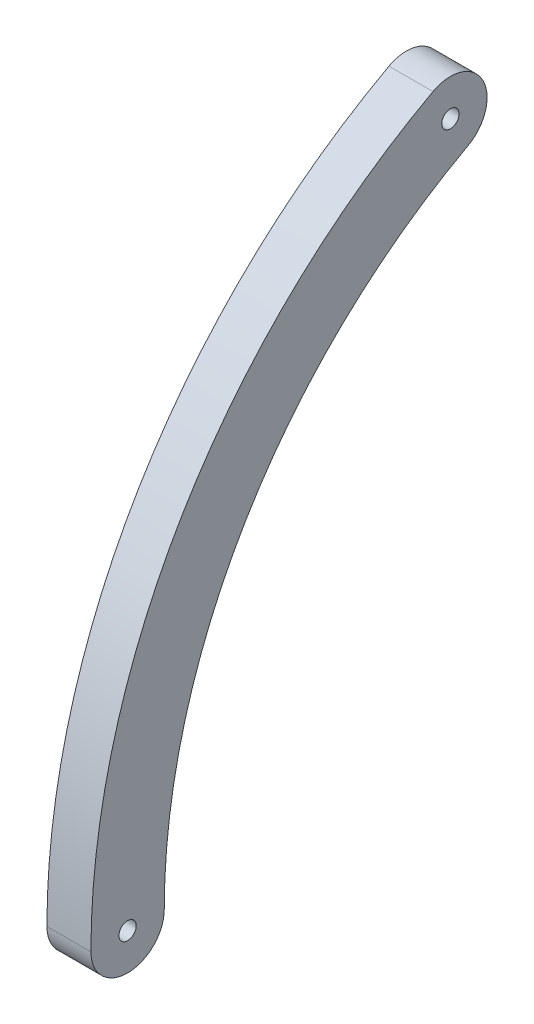
SolidWorks part; units mm, degrees
material "ABS"
ref_plane "Front Plane" through (0, 0, 0) normal (0, 0, 1) x (1, 0, 0)
ref_plane "Top Plane" through (0, 0, 0) normal (0, 1, 0) x (1, 0, 0)
ref_plane "Right Plane" through (0, 0, 0) normal (1, 0, 0) x (0, 0, -1)
sketch "Esquisse1" plane through (0, 0, 0) normal (1, 0, 0) x (0, 0, -1)
  arc A0 (-50.165, 0) -> (-23.8739, 44.1199) centre (0, 0) cw
  arc A1 (-56.515, 0) -> (-26.8959, 49.7047) centre (0, 0) cw
  arc A2 (-56.515, 0) -> (-50.165, 0) centre (-53.34, 0) ccw
  arc A3 (-23.8739, 44.1199) -> (-26.8959, 49.7047) centre (-25.3849, 46.9123) ccw
  circle A4 centre (-53.34, 0) radius 0.75
  circle A5 centre (-25.3849, 46.9123) radius 0.75
  dimension "D1" = 3.175
  dimension "D4" = 1.5
  dimension "D5" = 1.5
  dimension "D2" = 54.61
  dimension "D3" = 53.34
extrude "Boss.-Extru.1" add sketch "Esquisse1" along normal blind 3.81
